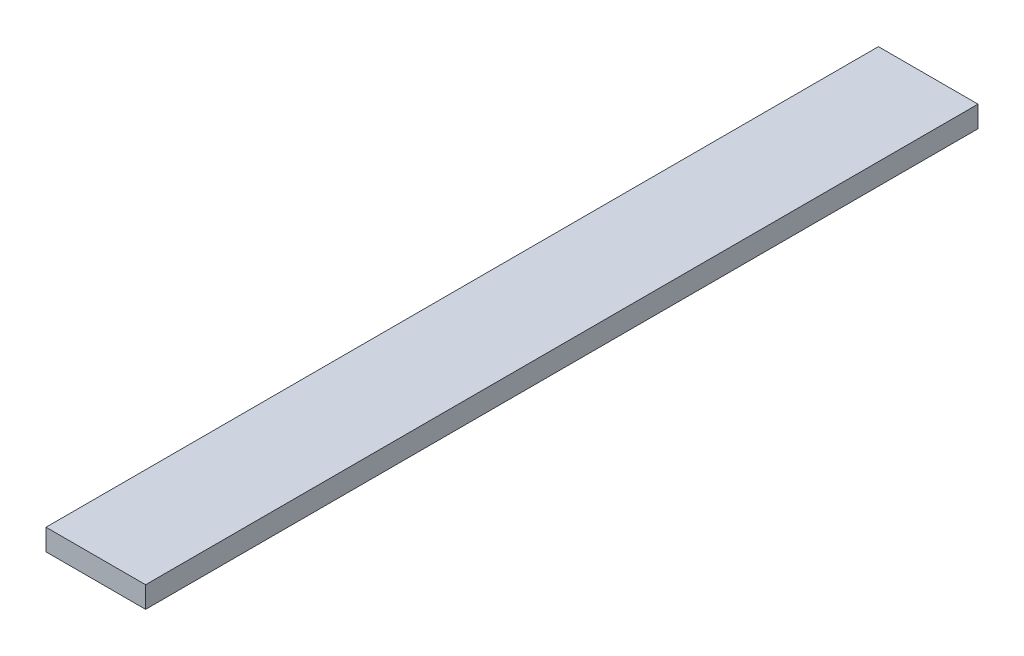
SolidWorks part; units mm, degrees
ref_plane "Plano frontal" through (0, 0, 0) normal (0, 0, 1) x (1, 0, 0)
ref_plane "Plano superior" through (0, 0, 0) normal (0, 1, 0) x (1, 0, 0)
ref_plane "Plano direito" through (0, 0, 0) normal (1, 0, 0) x (0, 0, -1)
sketch "Esboço1" plane through (0, 0, 0) normal (0, 0, 1) x (1, 0, 0)
  line L1 (35, 7.5) -> (-35, 7.5)
  line L2 (35, 7.5) -> (35, -7.5)
  line L3 (35, -7.5) -> (-35, -7.5)
  line L4 (-35, 7.5) -> (-35, -7.5)
  line L5 (35, 7.5) -> (-35, -7.5) construction
  line L6 (35, -7.5) -> (-35, 7.5) construction
  point P0 (0, 0)
  dimension "D1" = 70
  dimension "D2" = 15
extrude "Ressalto-extrusão1" add sketch "Esboço1" along normal blind 585
sketch "Esboço2" plane through (0, 7.5, 0) normal (0, 1, 0) x (1, 0, 0)
  line L0 (-35, -292.5) -> (35, -292.5) construction
  line L1 (-35, -585) -> (-35, 0) construction
  line L2 (35, -585) -> (35, 0) construction
  line L3 (0, -585) -> (0, 0) construction
  line L4 (35, -585) -> (-35, -585) construction
  line L5 (-35, -535) -> (35, -535) construction
  line L6 (-35, -50) -> (35, -50) construction
  line L7 (35, 0) -> (-35, 0) construction
  dimension "D1" = 50
  dimension "D2" = 50
sketch "Esboço3" plane through (0, 7.5, 0) normal (0, 1, 0) x (1, 0, 0)
  line L0 (-35, -50) -> (35, -50) construction
  line L1 (35, -585) -> (35, 0) construction
  line L2 (-35, -585) -> (-35, 0) construction
  line L3 (-33.7, -50) -> (-35, -50) construction
  line L4 (35, 0) -> (-35, 0) construction
  line L5 (-20, -50) -> (-20, -80.9365) construction
  dimension "D1" = 50
  dimension "D2" = 15
sketch "Esboço4" plane through (0, 7.5, 0) normal (0, 1, 0) x (1, 0, 0)
  line L1 (2.9, -511.4) -> (-21.3, -511.4) construction
  line L2 (2.9, -511.4) -> (2.9, -414) construction
  line L3 (2.9, -414) -> (-21.3, -414) construction
  line L4 (-21.3, -511.4) -> (-21.3, -414) construction
  circle A0 centre (-4.6, -426.583) radius 2.5 construction
  circle A1 centre (-4.6, -490.7969) radius 2.5 construction
